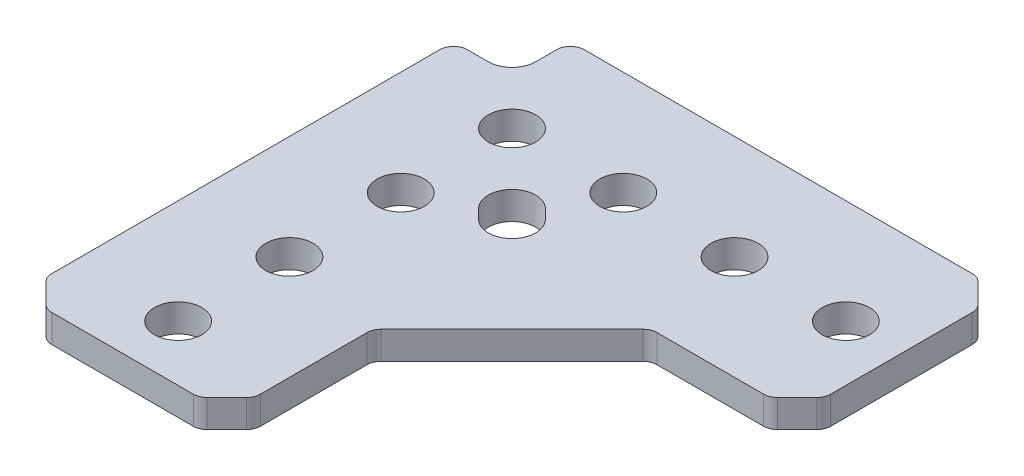
SolidWorks part; units mm, degrees
ref_plane "Front Plane" through (0, 0, 0) normal (0, 0, 1) x (1, 0, 0)
ref_plane "Top Plane" through (0, 0, 0) normal (0, 1, 0) x (1, 0, 0)
ref_plane "Right Plane" through (0, 0, 0) normal (1, 0, 0) x (0, 0, -1)
ref_plane "Plane1" through (0, 2, 0) normal (0, 1, 0) x (1, 0, 0)
sketch "Sketch1" plane through (0, 2, 0) normal (0, 1, 0) x (1, 0, 0)
  line L0 (4.4548, -6.8589) -> (3.7979, -6.2021)
  line L1 (6.2021, -3.7979) -> (6.8589, -4.4548)
  line L2 (26.2929, -7.2071) -> (27.7071, -5.7929)
  line L3 (28, -5.0858) -> (28, 5.0858)
  line L4 (27.7071, 5.7929) -> (26.2929, 7.2071)
  line L5 (25.5858, 7.5) -> (-2.3, 7.5)
  line L6 (-3.3, 6.5) -> (-3.3, 5)
  line L7 (-5, 3.3) -> (-6.5, 3.3)
  line L8 (-7.5, 2.3) -> (-7.5, -25.5858)
  line L9 (-7.2071, -26.2929) -> (-5.7929, -27.7071)
  line L10 (-5.0858, -28) -> (5.0858, -28)
  line L11 (5.7929, -27.7071) -> (7.2071, -26.2929)
  line L12 (7.5, -25.5858) -> (7.5, -17.9142)
  line L13 (7.7929, -17.2071) -> (17.2071, -7.7929)
  line L14 (17.9142, -7.5) -> (25.5858, -7.5)
  circle A0 centre (0, -16) radius 1.7
  circle A1 centre (0, -24) radius 1.7
  circle A2 centre (24, 0) radius 1.7
  circle A3 centre (16, 0) radius 1.7
  circle A4 centre (0, 0) radius 1.7
  arc A5 (6.8589, -4.4548) -> (4.4548, -6.8589) centre (5.6569, -5.6569) cw
  arc A6 (3.7979, -6.2021) -> (6.2021, -3.7979) centre (5, -5) cw
  circle A7 centre (8, 0) radius 1.7
  arc A8 (27.7071, -5.7929) -> (28, -5.0858) centre (27, -5.0858) ccw
  arc A9 (28, 5.0858) -> (27.7071, 5.7929) centre (27, 5.0858) ccw
  arc A10 (26.2929, 7.2071) -> (25.5858, 7.5) centre (25.5858, 6.5) ccw
  arc A11 (-2.3, 7.5) -> (-3.3, 6.5) centre (-2.3, 6.5) ccw
  arc A12 (-3.3, 5) -> (-5, 3.3) centre (-5, 5) cw
  arc A13 (-6.5, 3.3) -> (-7.5, 2.3) centre (-6.5, 2.3) ccw
  arc A14 (-7.5, -25.5858) -> (-7.2071, -26.2929) centre (-6.5, -25.5858) ccw
  arc A15 (-5.7929, -27.7071) -> (-5.0858, -28) centre (-5.0858, -27) ccw
  arc A16 (5.0858, -28) -> (5.7929, -27.7071) centre (5.0858, -27) ccw
  arc A17 (7.2071, -26.2929) -> (7.5, -25.5858) centre (6.5, -25.5858) ccw
  arc A18 (7.5, -17.9142) -> (7.7929, -17.2071) centre (8.5, -17.9142) cw
  arc A19 (17.2071, -7.7929) -> (17.9142, -7.5) centre (17.9142, -8.5) cw
  arc A20 (25.5858, -7.5) -> (26.2929, -7.2071) centre (25.5858, -6.5) ccw
  circle A21 centre (0, -8) radius 1.7
extrude "Boss-Extrude1" add sketch "Sketch1" against normal blind 2
